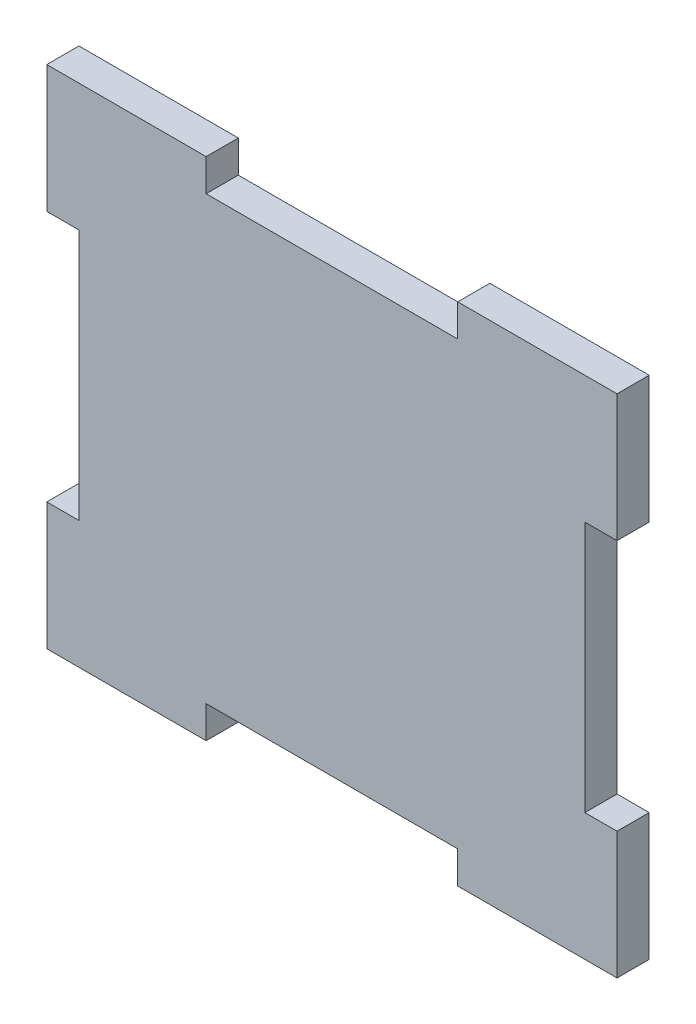
SolidWorks part; units mm, degrees
ref_plane "Front Plane" through (0, 0, 0) normal (0, 0, 1) x (1, 0, 0)
ref_plane "Top Plane" through (0, 0, 0) normal (0, 1, 0) x (1, 0, 0)
ref_plane "Right Plane" through (0, 0, 0) normal (1, 0, 0) x (0, 0, -1)
sketch "Sketch1" plane through (0, 0, 0) normal (0, 0, 1) x (1, 0, 0)
  line L1 (-56.36, 50) -> (56.36, 50)
  line L2 (-56.36, 50) -> (-56.36, -50)
  line L3 (-56.36, -50) -> (56.36, -50)
  line L4 (56.36, 50) -> (56.36, -50)
  line L5 (-56.36, 50) -> (56.36, -50) construction
  line L6 (-56.36, -50) -> (56.36, 50) construction
  point P0 (0, 0)
  dimension "D1" = 100
  dimension "D2" = 112.72
extrude "Boss-Extrude1" add sketch "Sketch1" along normal blind 6.36
sketch "Sketch2" [suppressed] plane through (0, 0, 3.36) normal (0, 0, 1) x (1, 0, 0)
  line L0 (50, 50) -> (-50, 50) construction
  line L1 (-25, 50) -> (25, 50)
  line L2 (-25, 50) -> (-25, 53.36)
  line L3 (-25, 53.36) -> (25, 53.36)
  line L4 (25, 50) -> (25, 53.36)
  line L5 (0, 0) -> (0, 53.36) construction
  line L6 (0, 0) -> (50, 0) construction
  line L7 (50, -50) -> (50, 50) construction
  dimension "D1" = 6.36
  dimension "D2" = 50
sketch "Sketch8" plane through (0, 0, 0) normal (0, 0, -1) x (-1, 0, 0)
  line L0 (0, 0) -> (0, 50) construction
  line L1 (-56.36, 50) -> (56.36, 50) construction
  line L2 (0, 0) -> (56.36, 0) construction
  line L3 (56.36, 50) -> (56.36, -50) construction
  line L5 (-25, 50) -> (25, 50)
  line L6 (-25, 50) -> (-25, 56.63)
  line L7 (-25, 56.63) -> (25, 56.63)
  line L8 (25, 50) -> (25, 56.63)
  dimension "D1" = 50
  dimension "D2" = 6.63
extrude "Boss-Extrude4" [suppressed] add sketch "Sketch8" against normal through all
mirror "Mirror4" [suppressed] about plane through (0, 0, 0) normal (0, 1, 0)
sketch "Sketch9" plane through (0, 0, 0) normal (0, 0, -1) x (-1, 0, 0)
  line L0 (0, 0) -> (56.36, 0) construction
  line L1 (56.36, 50) -> (56.36, -50) construction
  line L3 (56.36, 25) -> (62.99, 25)
  line L4 (56.36, 25) -> (56.36, -25)
  line L5 (56.36, -25) -> (62.99, -25)
  line L6 (62.99, 25) -> (62.99, -25)
  dimension "D1" = 50
  dimension "D2" = 6.63
extrude "Boss-Extrude5" [suppressed] add sketch "Sketch9" against normal through all
mirror "Mirror5" [suppressed] about plane through (0, 0, 0) normal (1, 0, 0)
sketch "Sketch10" plane through (0, 0, 6.36) normal (0, 0, 1) x (1, 0, 0)
  line L0 (0, 0) -> (0, 50) construction
  line L1 (56.36, 50) -> (-56.36, 50) construction
  line L3 (-24.865, 50) -> (24.865, 50)
  line L4 (-24.865, 50) -> (-24.865, 43.64)
  line L5 (-24.865, 43.64) -> (24.865, 43.64)
  line L6 (24.865, 50) -> (24.865, 43.64)
  dimension "D1" = 6.36
  dimension "D2" = 49.73
extrude "Cut-Extrude1" cut sketch "Sketch10" against normal through all
mirror "Mirror6" about plane through (0, 0, 0) normal (0, 1, 0) of "Cut-Extrude1"
sketch "Sketch11" plane through (0, 0, 6.36) normal (0, 0, 1) x (1, 0, 0)
  line L0 (0, 0) -> (56.36, 0) construction
  line L1 (56.36, -50) -> (56.36, 50) construction
  line L3 (56.36, 24.865) -> (50, 24.865)
  line L4 (56.36, 24.865) -> (56.36, -24.865)
  line L5 (56.36, -24.865) -> (50, -24.865)
  line L6 (50, 24.865) -> (50, -24.865)
  dimension "D1" = 6.36
  dimension "D2" = 49.73
extrude "Cut-Extrude2" cut sketch "Sketch11" against normal through all
mirror "Mirror7" about plane through (0, 0, 0) normal (1, 0, 0) of "Cut-Extrude2"
sketch "Sketch12" plane through (0, 0, 6.36) normal (0, 0, 1) x (1, 0, 0)
  line L0 (-56.36, -24.865) -> (-56.36, -50) construction
  line L1 (-56.36, -50) -> (-24.865, -50) construction
  line L2 (-37.3045, -26.1405) -> (-37.3045, 22.133) construction
  line L3 (-6.1998, 6.8595) -> (-6.1998, -21.0405) construction
  circle A0 centre (-37.3045, -26.1405) radius 1600
  circle A1 centre (-34.0001, 22.133) radius 3.3045
  circle A2 centre (-6.1998, -21.0405) radius 1.6
  circle A3 centre (-6.1998, 6.8595) radius 1.6
  dimension "D1" = 3200
  dimension "D2" = 19.0555
  dimension "D3" = 23.8595
  dimension "D4" = 6.6089
  dimension "D5" = 48.2735
  dimension "D6" = 3.2
  dimension "D7" = 5.1
  dimension "D8" = 3.2
  dimension "D9" = 27.8002
  dimension "D10" = 27.9
extrude "Cut-Extrude3" [suppressed] cut sketch "Sketch12" against normal blind 10
sketch "Sketch13" plane through (0, 0, 6.36) normal (0, 0, 1) x (1, 0, 0)
  line L0 (32.3057, -17.2496) -> (7.7192, -17.2496) construction
  line L1 (56.36, -50) -> (56.36, -24.865) construction
  line L2 (24.865, -50) -> (56.36, -50) construction
  circle A0 centre (32.3057, -17.2496) radius 2
  circle A1 centre (-9.9751, 3.9716) radius 2
  circle A2 centre (-9.9751, -38.4708) radius 2
  dimension "D1" = 4
  dimension "D2" = 42.4424
  dimension "D3" = 42.2808
  dimension "D4" = 24.0543
  dimension "D5" = 32.7504
extrude "Cut-Extrude4" [suppressed] cut sketch "Sketch13" against normal blind 10
sketch "Sketch18" plane through (0, 0, 0) normal (0, 0, -1) x (-1, 0, 0)
  line L0 (-37.32, -4.7) -> (-37.32, 6.3)
  line L1 (-37.32, 6.3) -> (-46.82, 6.3)
  line L2 (-46.82, 6.3) -> (-46.82, -4.7)
  line L3 (-46.82, -4.7) -> (-37.32, -4.7)
  line L24 (-50, 24.865) -> (-50, -24.865) construction
  line L25 (-56.36, 50) -> (-24.865, 50) construction
  dimension "D1" = 3.18
  dimension "D2" = 9.5
  dimension "D3" = 11
  dimension "D4" = 43.7
extrude "Cut-Extrude5" [suppressed] cut sketch "Sketch18" against normal blind 10
equation "\"Sheet Thickness\"= 6.36mm"
equation "\"Height\"= 100mm"
equation "\"Length\"= 200mm"
equation "\"Width\"= 100mm"
equation "\"D1@Boss-Extrude1\"=\"Sheet Thickness\""
equation "\"D1@Sketch2\"=\"Sheet Thickness\""
equation "\"D2@Sketch2\"=\"Height\"/2"
equation "\"Kerf\"= .27mm"
equation "\"D2@Sketch9\" = \"Sheet Thickness\"+\"Kerf\""
equation "\"D1@Sketch9\"   = \"Height\"/2"
equation "\"D1@Sketch8\"   = \"Width\"/2"
equation "\"D2@Sketch8\" = \"Sheet Thickness\"+\"Kerf\""
equation "\"D1@Sketch10\"  = \"Sheet Thickness\""
equation "\"D2@Sketch10\"    = \"Width\"/2 - \"Kerf\""
equation "\"D1@Sketch11\"  = \"Sheet Thickness\""
equation "\"D2@Sketch11\"  = \"Height\"/2 - \"Kerf\""
